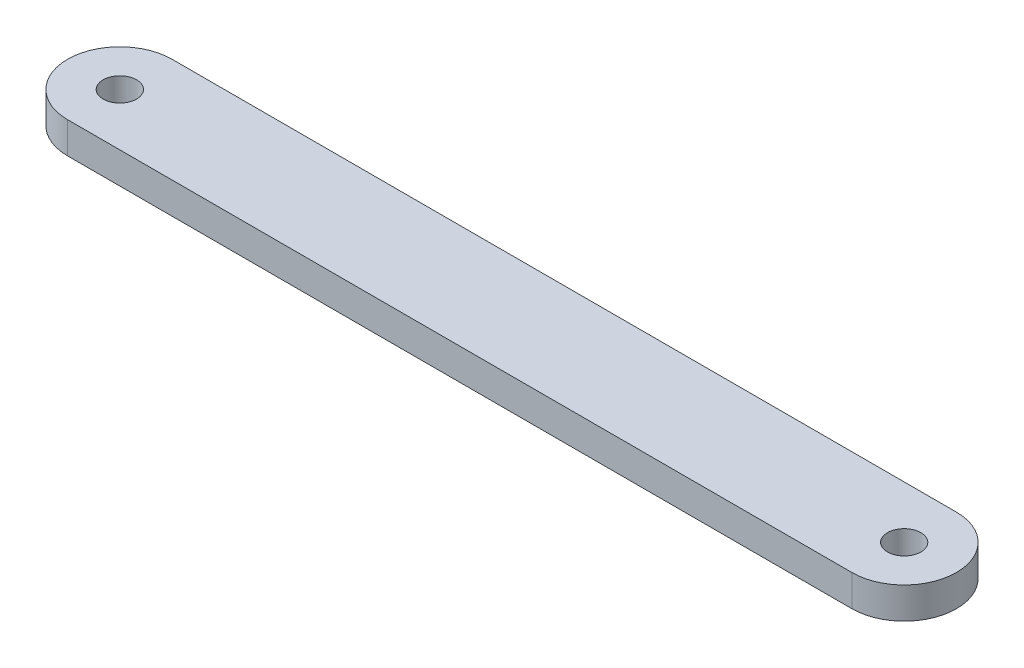
SolidWorks part; units mm, degrees
ref_plane "正面" through (0, 0, 0) normal (0, 0, 1) x (1, 0, 0)
ref_plane "平面" through (0, 0, 0) normal (0, 1, 0) x (1, 0, 0)
ref_plane "右側面" through (0, 0, 0) normal (1, 0, 0) x (0, 0, -1)
sketch "ｽｹｯﾁ1" plane through (0, 0, 0) normal (0, 1, 0) x (1, 0, 0)
  line L0 (0, 0) -> (110, 0) construction
  line L1 (0, -5) -> (75, -5)
  line L3 (0, 5) -> (75, 5)
  circle A0 centre (0, 0) radius 1.6
  circle A1 centre (75, 0) radius 1.6
  arc A2 (0, 5) -> (0, -5) centre (0, 0) ccw
  arc A3 (75, -5) -> (75, 5) centre (75, 0) ccw
  point P1 (0, 0)
  dimension "D5" = 3.2
  dimension "D1" = 5
  dimension "D2" = 10
  dimension "D4" = 75
extrude "ﾎﾞｽ - 押し出し1" add sketch "ｽｹｯﾁ1" along normal blind 3
